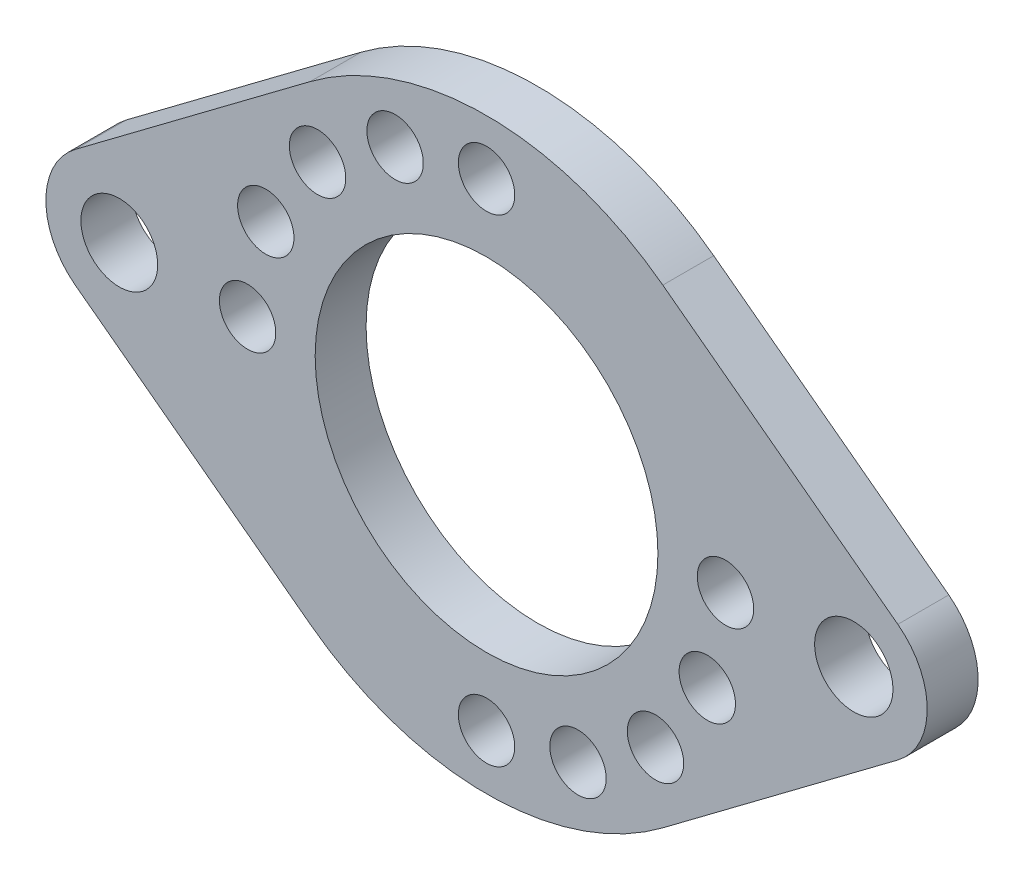
SolidWorks part; units mm, degrees
ref_plane "Front" through (0, 0, 0) normal (0, 0, 1) x (1, 0, 0)
ref_plane "Top" through (0, 0, 0) normal (0, 1, 0) x (1, 0, 0)
ref_plane "Right" through (0, 0, 0) normal (1, 0, 0) x (0, 0, -1)
sketch "Sketch1" plane through (0, 0, 0) normal (0, 0, 1) x (1, 0, 0)
  line L0 (-26.67, -3.81) -> (-11.43, -15.24)
  line L1 (11.43, -15.24) -> (26.67, -3.81)
  line L2 (26.67, 3.81) -> (11.43, 15.24)
  line L3 (-11.43, 15.24) -> (-26.67, 3.81)
  circle A0 centre (0, 0) radius 11.1125
  arc A1 (-26.67, 3.81) -> (-26.67, -3.81) centre (-23.8125, 0) ccw
  arc A2 (-11.43, -15.24) -> (11.43, -15.24) centre (0, 0) ccw
  arc A3 (26.67, -3.81) -> (26.67, 3.81) centre (23.8125, 0) ccw
  arc A4 (11.43, 15.24) -> (-11.43, 15.24) centre (0, 0) ccw
  circle A5 centre (0, 15.494) radius 1.8288
  circle A6 centre (-15.494, 0) radius 1.8288
  circle A7 centre (-14.3146, 5.9293) radius 1.8288
  circle A8 centre (-5.9293, 14.3146) radius 1.8288
  circle A9 centre (-10.9559, 10.9559) radius 1.8288
  circle A10 centre (0, -15.494) radius 1.8288
  circle A11 centre (15.494, 0) radius 1.8288
  circle A12 centre (14.3146, -5.9293) radius 1.8288
  circle A13 centre (5.9293, -14.3146) radius 1.8288
  circle A14 centre (10.9559, -10.9559) radius 1.8288
  circle A16 centre (-23.8125, 0) radius 2.4892
  circle A19 centre (23.8125, 0) radius 2.54
  circle A20 centre (0, 0) radius 23.8125 construction
  dimension "D2" = 47.625
extrude "Boss-Extrude1" add sketch "Sketch1" along normal blind 3.302
